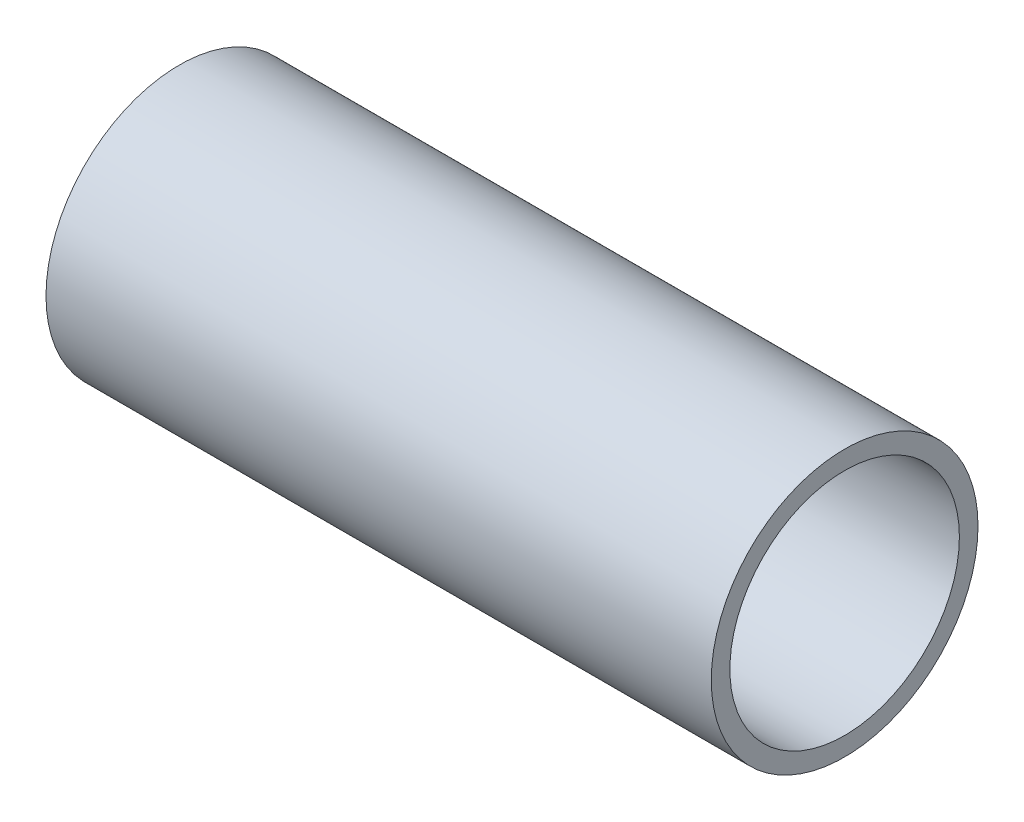
SolidWorks part; units mm, degrees
ref_plane "Front Plane" through (0, 0, 0) normal (0, 0, 1) x (1, 0, 0)
ref_plane "Top Plane" through (0, 0, 0) normal (0, 1, 0) x (1, 0, 0)
ref_plane "Right Plane" through (0, 0, 0) normal (1, 0, 0) x (0, 0, -1)
sketch "Sketch1" plane through (0, 0, 0) normal (0, 1, 0) x (1, 0, 0)
  line L0 (0, 0) -> (-214.5, 0)
  line L1 (-214.5, 0) -> (-214.5, 37)
  line L2 (-214.5, 37) -> (0, 37)
  line L3 (0, 37) -> (0, 0)
  line L4 (-214.5, 37) -> (-214.5, 43)
  line L5 (-214.5, 43) -> (0, 43)
  line L6 (0, 43) -> (0, 37)
  dimension "D1" = 37
  dimension "D2" = 214.5
revolve "Revolve1" add sketch "Sketch1" angle 360 about L0
